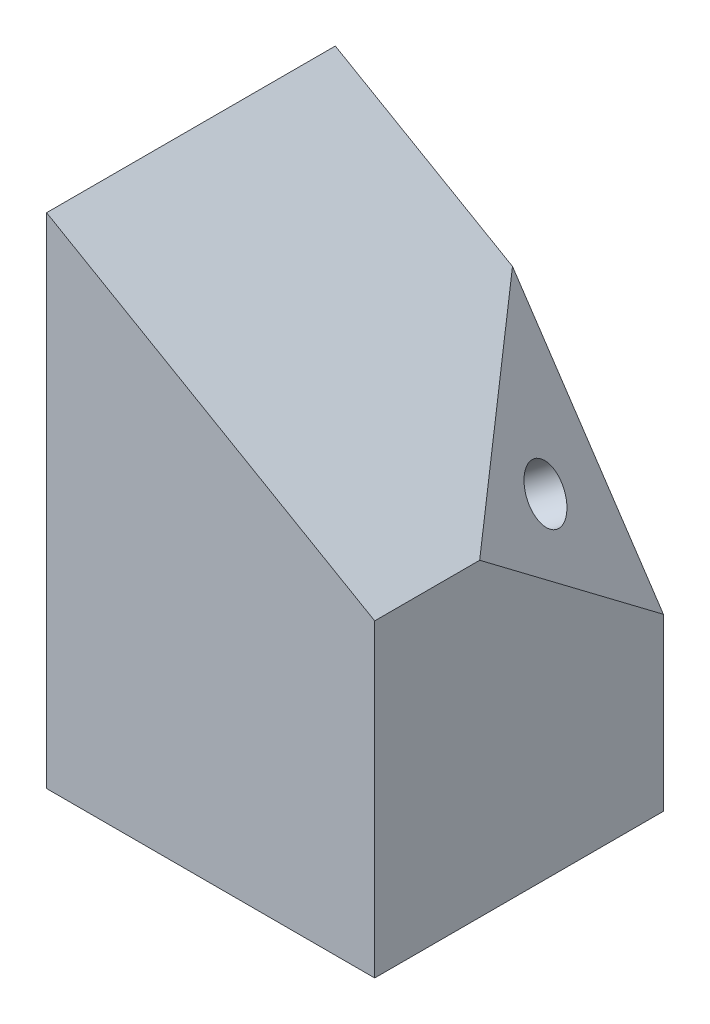
SolidWorks part; units mm, degrees
ref_plane "Front Plane" through (0, 0, 0) normal (0, 0, 1) x (1, 0, 0)
ref_plane "Top Plane" through (0, 0, 0) normal (0, 1, 0) x (1, 0, 0)
ref_plane "Right Plane" through (0, 0, 0) normal (1, 0, 0) x (0, 0, -1)
sketch "Sketch2" plane through (0, 0, 0) normal (0, 1, 0) x (1, 0, 0)
  line L1 (-50, 0) -> (0, 0)
  line L2 (-50, 0) -> (-50, 44)
  line L3 (-50, 44) -> (0, 44)
  line L4 (0, 0) -> (0, 44)
  point P4 (0, 0)
  dimension "D1" = 44
  dimension "D2" = 50
extrude "Boss-Extrude2" add sketch "Sketch2" along normal blind 76
sketch "Sketch3" plane through (0, 0, 0) normal (0, 0, 1) x (1, 0, 0)
  line L0 (-50, 76) -> (0, 47.1325)
  line L1 (0, 76) -> (0, 0) construction
  line L2 (-50, 76) -> (0, 76)
  line L3 (0, 76) -> (0, 47.1325)
  dimension "D1" = 30
extrude "Cut-Extrude1" cut sketch "Sketch3" against normal blind 76
sketch "Sketch6" plane through (0, 0, 0) normal (1, 0, 0) x (0, 0, -1)
  line L0 (44, 47.1325) -> (0, 47.1325) construction
  point P0 (16, 47.1325)
  dimension "D1" = 16
sketch "Sketch7" plane through (0, 0, -44) normal (0, 0, -1) x (-1, 0, 0)
  line L0 (50, 76) -> (0, 47.1325) construction
  point P0 (23, 60.4115)
  dimension "D1" = 27
sketch "Sketch8" plane through (0, 0, 0) normal (1, 0, 0) x (0, 0, -1)
  line L0 (44, 47.1325) -> (44, 0) construction
  point P0 (44, 26)
  point P1 (0, 0)
  dimension "D1" = 26
ref_plane "Plane13" through (23.2622, 15.548, -11.7345) normal (-0.7667, -0.5124, 0.3868) x (0.3215, 0.2149, 0.9222)
sketch "Sketch10" plane through (23.2622, 15.548, -11.7345) normal (-0.7667, -0.5124, 0.3868) x (0.3215, 0.2149, 0.9222)
  line L0 (-4.6254, 39.1856) -> (-34.9882, 63.0065)
  line L1 (-34.9882, 63.0065) -> (-34.9882, 21.6162)
  line L2 (-34.9882, 21.6162) -> (-4.6254, 39.1856)
extrude "Cut-Extrude2" cut sketch "Sketch10" against normal blind 76
sketch "Sketch12" plane through (0, 0, 0) normal (1, 0, 0) x (0, 0, -1)
  line L0 (44, 26) -> (16, 47.1325) construction
  point P0 (28, 38.0757)
  point P1 (27.9717, 38.0971)
  dimension "D1" = 12
sketch "Sketch13" plane through (0, 0, -44) normal (0, 0, -1) x (-1, 0, 0)
  line L0 (23, 60.4115) -> (0, 26) construction
  point P0 (11, 42.4577)
  dimension "D1" = 12
sketch "Sketch14" plane through (23.2622, 15.548, -11.7345) normal (-0.7667, -0.5124, 0.3868) x (0.3215, 0.2149, 0.9222)
  line L0 (-34.9882, 41.4115) -> (-4.6254, 39.1856)
  line L1 (-17.638, 31.6558) -> (-34.9882, 63.0065)
  line L2 (-34.9882, 63.0065) -> (-34.9882, 21.6162) construction
  circle A0 centre (-22.5317, 40.4983) radius 4
  point P12 (-22.3979, 40.4885)
  point P13 (0, 0)
  point P14 (0, 0)
  point P15 (-34.9882, 63.0065)
  dimension "D1" = 8
extrude "Cut-Extrude3" cut sketch "Sketch14" along normal blind 20 contours A0
